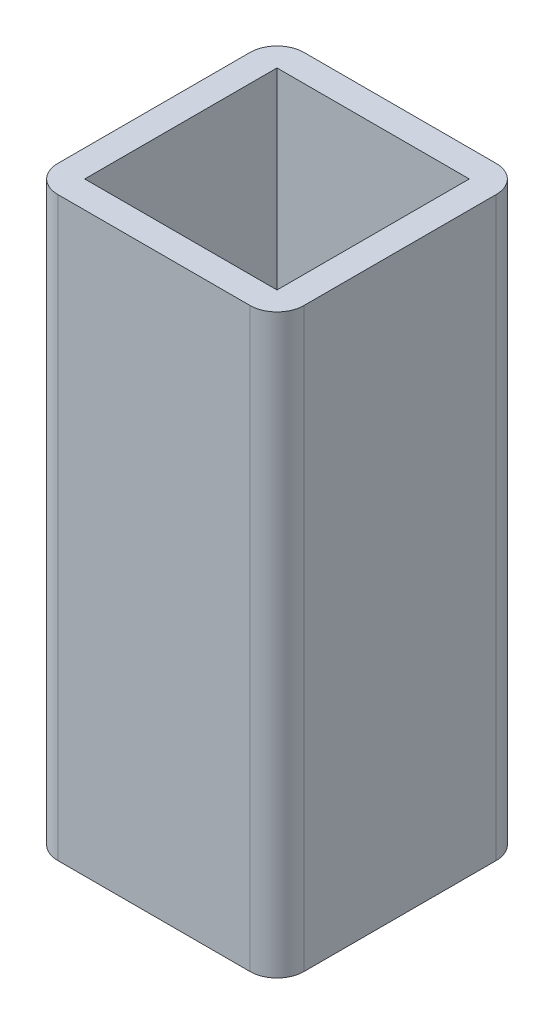
SolidWorks part; units mm, degrees
ref_plane "Front Plane" through (0, 0, 0) normal (0, 0, 1) x (1, 0, 0)
ref_plane "Top Plane" through (0, 0, 0) normal (0, 1, 0) x (1, 0, 0)
ref_plane "Right Plane" through (0, 0, 0) normal (1, 0, 0) x (0, 0, -1)
sketch "Sketch1" plane through (0, 0, 0) normal (0, 1, 0) x (1, 0, 0)
  line L1 (2.8, 0) -> (22.8, 0)
  line L2 (0, -2.8) -> (0, -22.8)
  line L3 (2.8, -25.6) -> (22.8, -25.6)
  line L4 (25.6, -2.8) -> (25.6, -22.8)
  arc A0 (22.8, 0) -> (25.6, -2.8) centre (22.8, -2.8) cw
  arc A1 (22.8, -25.6) -> (25.6, -22.8) centre (22.8, -22.8) ccw
  arc A2 (0, -22.8) -> (2.8, -25.6) centre (2.8, -22.8) ccw
  arc A3 (2.8, 0) -> (0, -2.8) centre (2.8, -2.8) ccw
  point P7 (25.6, 0)
  point P10 (25.6, -25.6)
  point P15 (0, 0)
  dimension "D2" = 2.8
  dimension "D1" = 25.6
extrude "Boss-Extrude1" add sketch "Sketch1" along normal blind 60
sketch "Sketch3" plane through (0, 0, 0) normal (0, -1, 0) x (-1, 0, 0)
  line L4 (-2.8, -2.8) -> (-22.8, -2.8)
  line L5 (-2.8, -2.8) -> (-2.8, -22.8)
  line L6 (-2.8, -22.8) -> (-22.8, -22.8)
  line L7 (-22.8, -2.8) -> (-22.8, -22.8)
  line L8 (-2.8, -2.8) -> (-22.8, -22.8) construction
  line L9 (-2.8, -22.8) -> (-22.8, -2.8) construction
  point P6 (-12.8, -12.8)
extrude "Cut-Extrude1" cut sketch "Sketch3" against normal blind 1040.5
